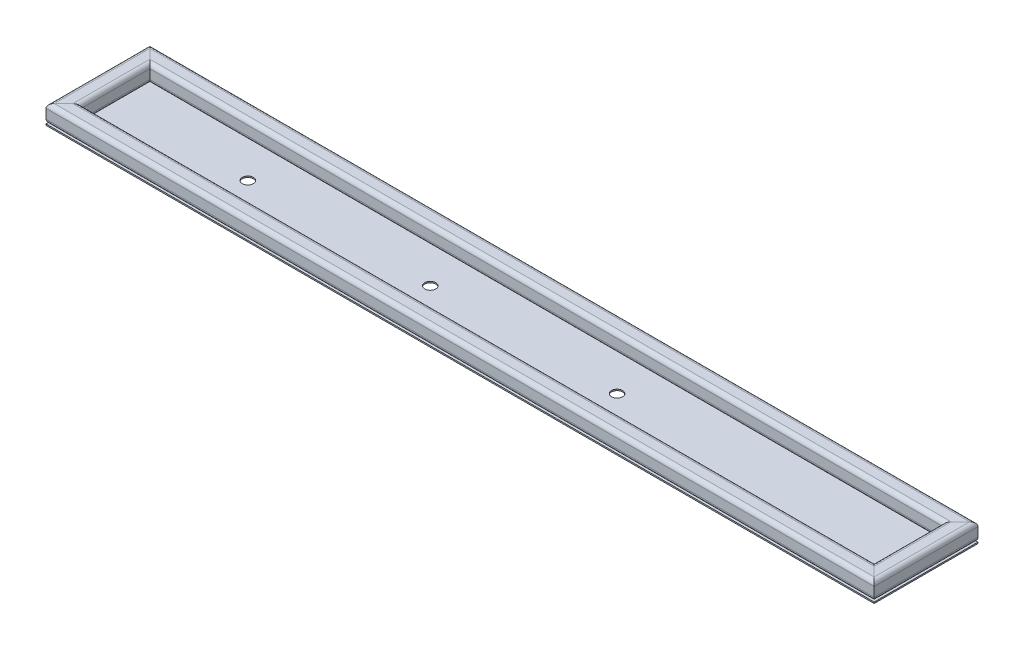
SolidWorks part; units mm, degrees
ref_plane "Alzado" through (0, 0, 0) normal (0, 0, 1) x (1, 0, 0)
ref_plane "Planta" through (0, 0, 0) normal (0, 1, 0) x (1, 0, 0)
ref_plane "Vista lateral" through (0, 0, 0) normal (1, 0, 0) x (0, 0, -1)
sketch "Croquis1" plane through (0, 0, 0) normal (0, 1, 0) x (1, 0, 0)
  line L1 (-598.2, 75) -> (598.2, 75)
  line L2 (-598.2, 75) -> (-598.2, -75)
  line L3 (-598.2, -75) -> (598.2, -75)
  line L4 (598.2, 75) -> (598.2, -75)
  line L5 (-598.2, 75) -> (598.2, -75) construction
  line L6 (-598.2, -75) -> (598.2, 75) construction
  point P0 (0, 0)
  dimension "D1" = 150
  dimension "D2" = 1196.4
other "Tubo cuadrado 2 X 2 X 0.25(1)"
ref_plane "Plano1" through (-585.5, 12.7, -75) normal (0, 0, 1) x (1, 0, 0)
sketch "Sketch1" plane through (-585.5, 12.7, -75) normal (0, 0, 1) x (1, 0, 0)
  line L0 (-6.7, -9.7) -> (6.7, -9.7)
  line L1 (-9.7, -6.7) -> (-9.7, 6.7)
  line L2 (6.7, 9.7) -> (-6.7, 9.7)
  line L3 (9.7, 6.7) -> (9.7, -6.7)
  line L4 (-6.7, -12.7) -> (6.7, -12.7)
  line L5 (-12.7, -6.7) -> (-12.7, 6.7)
  line L6 (6.7, 12.7) -> (-6.7, 12.7)
  line L7 (12.7, 6.7) -> (12.7, -6.7)
  line L8 (0, 0) -> (9.7, 0) construction
  line L9 (0, 0) -> (0, 9.7) construction
  arc A0 (12.7, 6.7) -> (6.7, 12.7) centre (6.7, 6.7) ccw
  arc A1 (6.7, -12.7) -> (12.7, -6.7) centre (6.7, -6.7) ccw
  arc A2 (-12.7, -6.7) -> (-6.7, -12.7) centre (-6.7, -6.7) ccw
  arc A3 (-6.7, 12.7) -> (-12.7, 6.7) centre (-6.7, 6.7) ccw
  arc A4 (-6.7, 9.7) -> (-9.7, 6.7) centre (-6.7, 6.7) ccw
  arc A5 (9.7, 6.7) -> (6.7, 9.7) centre (6.7, 6.7) ccw
  arc A6 (6.7, -9.7) -> (9.7, -6.7) centre (6.7, -6.7) ccw
  arc A7 (-9.7, -6.7) -> (-6.7, -9.7) centre (-6.7, -6.7) ccw
  point P3 (0, 12.7)
  point P4 (12.7, 0)
  point P5 (0, -12.7)
  point P6 (-12.7, 0)
  point P7 (-12.7, 12.7)
  point P8 (-12.7, -12.7)
  point P33 (0, 0)
  point P35 (12.7, -12.7)
  point P36 (12.7, 12.7)
  point P37 (0, 0)
  dimension "D1" = 6
  dimension "Thickness" = 3
  dimension "V_leg" = 25.4
sketch "Croquis3" plane through (0, 0, 0) normal (0, -1, 0) x (1, 0, 0)
  line L1 (598.2, 75) -> (-598.2, 75)
  line L2 (598.2, 75) -> (598.2, -75)
  line L3 (598.2, -75) -> (-598.2, -75)
  line L4 (-598.2, 75) -> (-598.2, -75)
  line L5 (598.2, 75) -> (-598.2, -75) construction
  line L6 (598.2, -75) -> (-598.2, 75) construction
  point P0 (0, 0)
extrude "Saliente-Extruir1" add sketch "Croquis3" along normal blind 1.9 separate body
ref_plane "Plano2" through (0, 0, 0) normal (0, 0, 1) x (1, 0, 0)
sketch "Croquis4" plane through (0, 0, 0) normal (0, 1, 0) x (1, 0, 0)
  circle A0 centre (-268.2099, 0) radius 7.9375
  circle A1 centre (-291.2099, 0.2449) radius 3.175
  circle A2 centre (-245.2099, -0.2449) radius 3.175
  circle A3 centre (-58.2099, 0) radius 7.9375
  circle A4 centre (-81.2099, 0.2449) radius 3.175
  circle A5 centre (-35.2099, -0.2449) radius 3.175
  circle A6 centre (151.7851, 0) radius 7.9375
  circle A7 centre (174.7851, -0.2449) radius 3.175
  circle A8 centre (128.7851, 0.2449) radius 3.175
sketch "Croquis5" plane through (0, 0, 0) normal (0, 1, 0) x (1, 0, 0)
  circle A1 centre (-381.5729, 0) radius 7.9375
  circle A3 centre (-118.0729, 0) radius 7.9375
  circle A7 centre (151.7851, 0) radius 7.9375
extrude "Cortar-Extruir1" cut sketch "Croquis5" against normal blind 10
